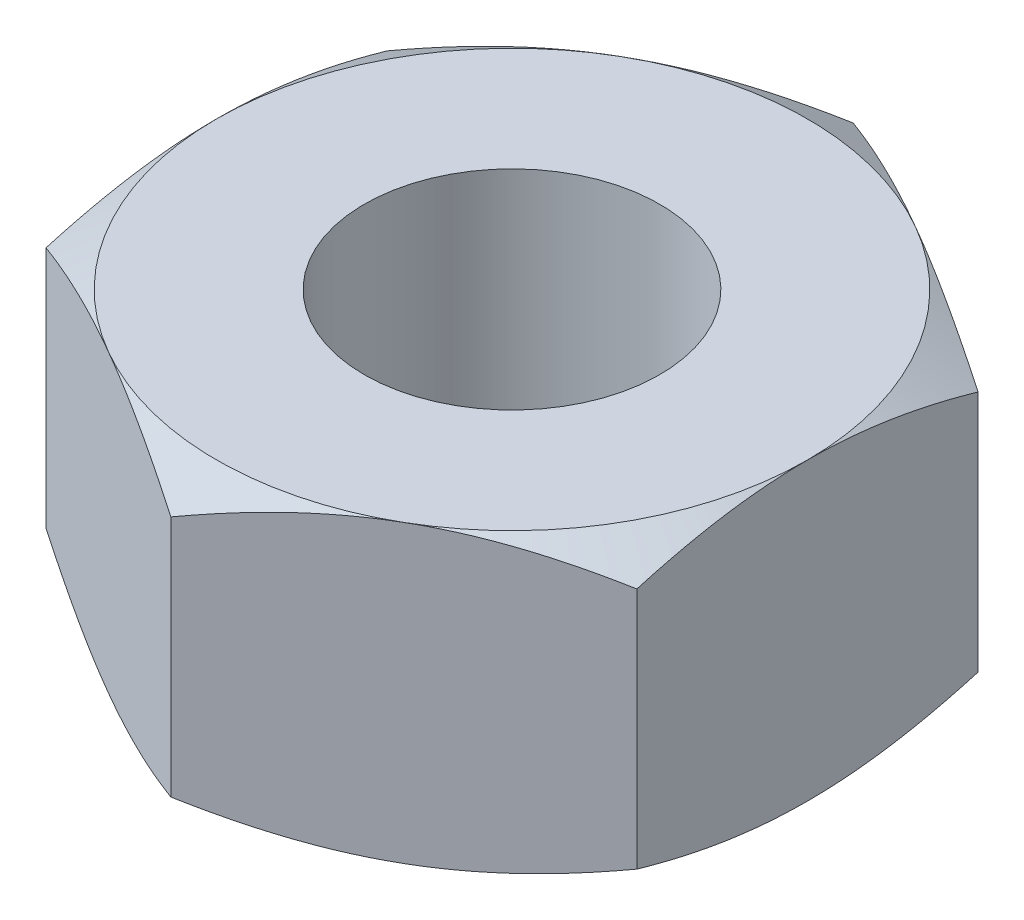
SolidWorks part; units mm, degrees
ref_plane "Front Plane" through (0, 0, 0) normal (0, 0, 1) x (1, 0, 0)
ref_plane "Top Plane" through (0, 0, 0) normal (0, 1, 0) x (1, 0, 0)
ref_plane "Right Plane" through (0, 0, 0) normal (1, 0, 0) x (0, 0, -1)
sketch "Sketch1" plane through (0, 0, 0) normal (0, 1, 0) x (1, 0, 0)
  line L1 (0, 2.3094) -> (-2, 1.1547)
  line L2 (-2, 1.1547) -> (-2, -1.1547)
  line L3 (-2, -1.1547) -> (0, -2.3094)
  line L4 (0, -2.3094) -> (2, -1.1547)
  line L5 (2, -1.1547) -> (2, 1.1547)
  line L6 (2, 1.1547) -> (0, 2.3094)
  circle A0 centre (0, 0) radius 1
  circle A1 centre (0, 0) radius 2 construction
  dimension "D1" = 2
  dimension "D2" = 4
extrude "Boss-Extrude1" add sketch "Sketch1" along normal blind 2
sketch "Sketch2" plane through (0, 2, 0) normal (0, 1, 0) x (1, 0, 0)
  circle A0 centre (0, 0) radius 2 construction
  circle A1 centre (0, 0) radius 2
extrude "Cut-Extrude1" cut sketch "Sketch2" against normal blind 2 draft 60 flip side to cut
sketch "Sketch3" plane through (0, 0, 0) normal (0, -1, 0) x (1, 0, 0)
  circle A0 centre (0, 0) radius 2 construction
  circle A1 centre (0, 0) radius 2
extrude "Cut-Extrude2" cut sketch "Sketch3" against normal blind 2 draft 60 flip side to cut
